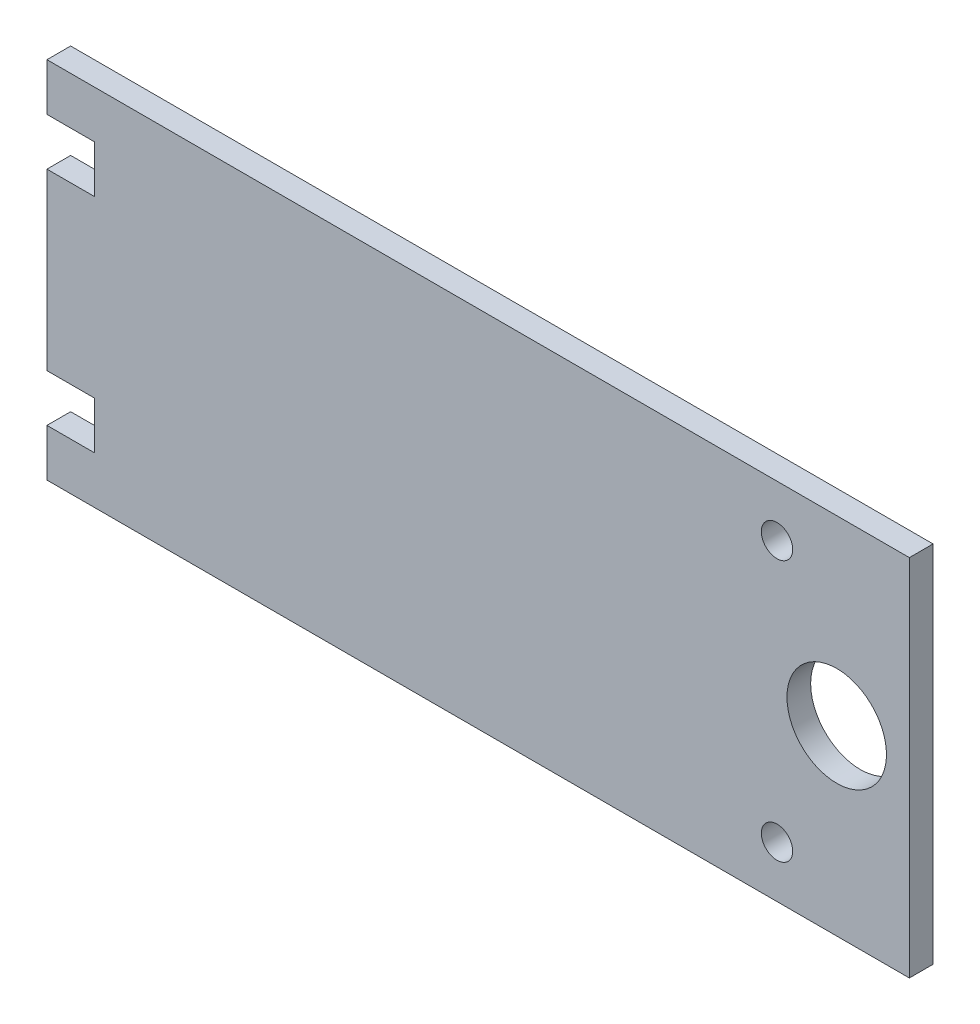
SolidWorks part; units mm, degrees
ref_plane "Front Plane" through (0, 0, 0) normal (0, 0, 1) x (1, 0, 0)
ref_plane "Top Plane" through (0, 0, 0) normal (0, 1, 0) x (1, 0, 0)
ref_plane "Right Plane" through (0, 0, 0) normal (1, 0, 0) x (0, 0, -1)
sketch "Sketch1" plane through (0, 0, 0) normal (0, 0, 1) x (1, 0, 0)
  line L1 (-57.785, 24.3948) -> (57.785, 24.3948)
  line L2 (-57.785, 24.3948) -> (-57.785, -24.3948)
  line L3 (-57.785, -24.3948) -> (57.785, -24.3948)
  line L4 (57.785, 24.3948) -> (57.785, -24.3948)
  line L5 (-57.785, 24.3948) -> (57.785, -24.3948) construction
  line L6 (-57.785, -24.3948) -> (57.785, 24.3948) construction
  point P0 (0, 0)
  dimension "D1" = 115.57
  dimension "D2" = 48.7897
extrude "Boss-Extrude1" add sketch "Sketch1" along normal blind 3.175
sketch "Sketch2" plane through (0, 0, 0) normal (0, 0, -1) x (-1, 0, 0)
  line L0 (57.785, -24.3948) -> (-57.785, -24.3948) construction
  line L1 (-57.785, -24.3948) -> (-57.785, 24.3948) construction
  line L2 (-57.785, 24.3948) -> (57.785, 24.3948) construction
  circle A0 centre (-40.0489, 17.5) radius 2.1019
  circle A1 centre (-40.0489, -17.5) radius 2.1019
  circle A2 centre (-48.0489, 0) radius 6.6675
  dimension "D1" = 13.335
  dimension "D2" = 4.2037
  dimension "D3" = 4.2037
  dimension "D4" = 6.8948
  dimension "D5" = 17.7361
  dimension "D6" = 9.7361
  dimension "D7" = 24.3948
  dimension "D8" = 6.8948
  dimension "D9" = 17.7361
extrude "Cut-Extrude1" cut sketch "Sketch2" against normal through all
sketch "Sketch3" plane through (0, 0, 3.175) normal (0, 0, 1) x (1, 0, 0)
  line L0 (-57.785, 18.0448) -> (-57.785, 11.6948)
  line L1 (-57.785, 18.0448) -> (-51.435, 18.0448)
  line L2 (-57.785, 11.6948) -> (-51.435, 11.6948)
  line L3 (-51.435, 18.0448) -> (-51.435, 11.6948)
  line L4 (-57.785, 24.3948) -> (-57.785, -24.3948) construction
  line L5 (-57.785, -11.6948) -> (-57.785, -18.0448)
  line L6 (-57.785, -11.6948) -> (-51.435, -11.6948)
  line L7 (-57.785, -18.0448) -> (-51.435, -18.0448)
  line L8 (-51.435, -11.6948) -> (-51.435, -18.0448)
  line L9 (57.785, 24.3948) -> (-57.785, 24.3948) construction
  line L10 (-57.785, -24.3948) -> (57.785, -24.3948) construction
  dimension "D1" = 6.35
  dimension "D2" = 6.35
  dimension "D3" = 6.35
  dimension "D4" = 6.35
extrude "Cut-Extrude2" cut sketch "Sketch3" against normal through all
